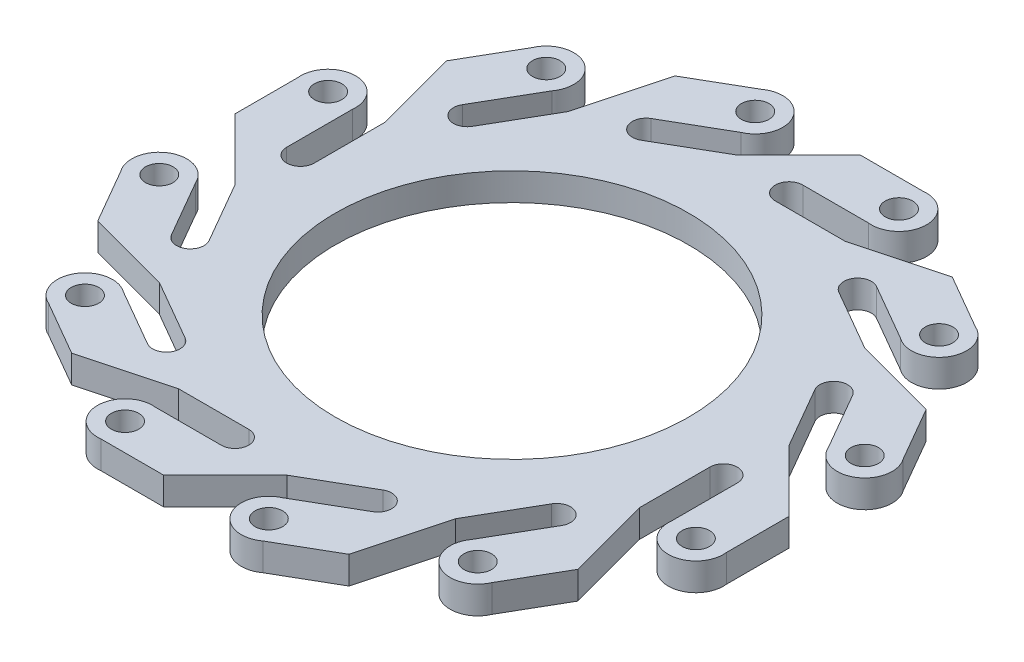
SolidWorks part; units mm, degrees
ref_plane "前视基准面" through (0, 0, 0) normal (0, 0, 1) x (1, 0, 0)
ref_plane "上视基准面" through (0, 0, 0) normal (0, 1, 0) x (1, 0, 0)
ref_plane "右视基准面" through (0, 0, 0) normal (1, 0, 0) x (0, 0, -1)
sketch "草图1" plane through (0, 0, 0) normal (0, 1, 0) x (1, 0, 0)
  line L0 (-31.2077, 0) -> (44.5556, 0) construction
  line L1 (0, 28.3069) -> (0, -34.4829) construction
  line L2 (7.1505, 22.7146) -> (2.5849, 22.7146)
  line L3 (7.1505, 18.7398) -> (2.3776, 18.7398)
  line L4 (2.3776, 16.7398) -> (7.4784, 16.7398)
  line L5 (10.429, 13.3082) -> (14.8463, 10.7579)
  line L6 (15.5624, 12.6539) -> (11.429, 15.0403)
  line L7 (17.5498, 16.0962) -> (13.5959, 18.379)
  line L8 (15.6859, 6.3108) -> (18.2362, 1.8934)
  line L9 (19.8043, 3.1774) -> (17.4179, 7.3108)
  line L10 (23.2466, 5.1648) -> (20.9639, 9.1187)
  line L11 (16.7398, -2.3776) -> (16.7398, -7.4784)
  line L12 (18.7398, -7.1505) -> (18.7398, -2.3776)
  line L13 (22.7146, -7.1505) -> (22.7146, -2.5849)
  line L14 (13.3082, -10.429) -> (10.7579, -14.8463)
  line L15 (12.6539, -15.5624) -> (15.0403, -11.429)
  line L16 (16.0962, -17.5498) -> (18.379, -13.5959)
  line L17 (6.3108, -15.6859) -> (1.8934, -18.2362)
  line L18 (3.1774, -19.8043) -> (7.3108, -17.4179)
  line L19 (5.1648, -23.2466) -> (9.1187, -20.9639)
  line L20 (-2.3776, -16.7398) -> (-7.4784, -16.7398)
  line L21 (-7.1505, -18.7398) -> (-2.3776, -18.7398)
  line L22 (-7.1505, -22.7146) -> (-2.5849, -22.7146)
  line L23 (-10.429, -13.3082) -> (-14.8463, -10.7579)
  line L24 (-15.5624, -12.6539) -> (-11.429, -15.0403)
  line L25 (-17.5498, -16.0962) -> (-13.5959, -18.379)
  line L26 (-15.6859, -6.3108) -> (-18.2362, -1.8934)
  line L27 (-19.8043, -3.1774) -> (-17.4179, -7.3108)
  line L28 (-23.2466, -5.1648) -> (-20.9639, -9.1187)
  line L29 (-16.7398, 2.3776) -> (-16.7398, 7.4784)
  line L30 (-18.7398, 7.1505) -> (-18.7398, 2.3776)
  line L31 (-22.7146, 7.1505) -> (-22.7146, 2.5849)
  line L32 (-13.3082, 10.429) -> (-10.7579, 14.8463)
  line L33 (-12.6539, 15.5624) -> (-15.0403, 11.429)
  line L34 (-16.0962, 17.5498) -> (-18.379, 13.5959)
  line L35 (-6.3108, 15.6859) -> (-1.8934, 18.2362)
  line L36 (-3.1774, 19.8043) -> (-7.3108, 17.4179)
  line L37 (-5.1648, 23.2466) -> (-9.1187, 20.9639)
  line L38 (2.5849, 22.7146) -> (-1.8934, 18.2362)
  line L39 (13.5959, 18.379) -> (7.4784, 16.7398)
  line L40 (20.9639, 9.1187) -> (14.8463, 10.7579)
  line L41 (22.7146, -2.5849) -> (18.2362, 1.8934)
  line L42 (18.379, -13.5959) -> (16.7398, -7.4784)
  line L43 (9.1187, -20.9639) -> (10.7579, -14.8463)
  line L44 (-2.5849, -22.7146) -> (1.8934, -18.2362)
  line L45 (-13.5959, -18.379) -> (-7.4784, -16.7398)
  line L46 (-20.9639, -9.1187) -> (-14.8463, -10.7579)
  line L47 (-22.7146, 2.5849) -> (-18.2362, -1.8934)
  line L48 (-18.379, 13.5959) -> (-16.7398, 7.4784)
  line L49 (-9.1187, 20.9639) -> (-10.7579, 14.8463)
  circle A0 centre (7.3746, 20.7272) radius 1
  circle A1 centre (0, 0) radius 22 construction
  arc A2 (7.1505, 22.7146) -> (7.1505, 18.7398) centre (7.3746, 20.7272) cw
  arc A3 (2.3776, 18.7398) -> (2.3776, 16.7398) centre (2.3776, 17.7398) ccw
  arc A4 (11.429, 15.0403) -> (10.429, 13.3082) centre (10.929, 14.1743) ccw
  arc A5 (17.5498, 16.0962) -> (15.5624, 12.6539) centre (16.7501, 14.263) cw
  circle A6 centre (16.7501, 14.263) radius 1
  arc A7 (17.4179, 7.3108) -> (15.6859, 6.3108) centre (16.5519, 6.8108) ccw
  arc A8 (23.2466, 5.1648) -> (19.8043, 3.1774) centre (21.6375, 3.977) cw
  circle A9 centre (21.6375, 3.977) radius 1
  arc A10 (18.7398, -2.3776) -> (16.7398, -2.3776) centre (17.7398, -2.3776) ccw
  arc A11 (22.7146, -7.1505) -> (18.7398, -7.1505) centre (20.7272, -7.3746) cw
  circle A12 centre (20.7272, -7.3746) radius 1
  arc A13 (15.0403, -11.429) -> (13.3082, -10.429) centre (14.1743, -10.929) ccw
  arc A14 (16.0962, -17.5498) -> (12.6539, -15.5624) centre (14.263, -16.7501) cw
  circle A15 centre (14.263, -16.7501) radius 1
  arc A16 (7.3108, -17.4179) -> (6.3108, -15.6859) centre (6.8108, -16.5519) ccw
  arc A17 (5.1648, -23.2466) -> (3.1774, -19.8043) centre (3.977, -21.6375) cw
  circle A18 centre (3.977, -21.6375) radius 1
  arc A19 (-2.3776, -18.7398) -> (-2.3776, -16.7398) centre (-2.3776, -17.7398) ccw
  arc A20 (-7.1505, -22.7146) -> (-7.1505, -18.7398) centre (-7.3746, -20.7272) cw
  circle A21 centre (-7.3746, -20.7272) radius 1
  arc A22 (-11.429, -15.0403) -> (-10.429, -13.3082) centre (-10.929, -14.1743) ccw
  arc A23 (-17.5498, -16.0962) -> (-15.5624, -12.6539) centre (-16.7501, -14.263) cw
  circle A24 centre (-16.7501, -14.263) radius 1
  arc A25 (-17.4179, -7.3108) -> (-15.6859, -6.3108) centre (-16.5519, -6.8108) ccw
  arc A26 (-23.2466, -5.1648) -> (-19.8043, -3.1774) centre (-21.6375, -3.977) cw
  circle A27 centre (-21.6375, -3.977) radius 1
  arc A28 (-18.7398, 2.3776) -> (-16.7398, 2.3776) centre (-17.7398, 2.3776) ccw
  arc A29 (-22.7146, 7.1505) -> (-18.7398, 7.1505) centre (-20.7272, 7.3746) cw
  circle A30 centre (-20.7272, 7.3746) radius 1
  arc A31 (-15.0403, 11.429) -> (-13.3082, 10.429) centre (-14.1743, 10.929) ccw
  arc A32 (-16.0962, 17.5498) -> (-12.6539, 15.5624) centre (-14.263, 16.7501) cw
  circle A33 centre (-14.263, 16.7501) radius 1
  arc A34 (-7.3108, 17.4179) -> (-6.3108, 15.6859) centre (-6.8108, 16.5519) ccw
  arc A35 (-5.1648, 23.2466) -> (-3.1774, 19.8043) centre (-3.977, 21.6375) cw
  circle A36 centre (-3.977, 21.6375) radius 1
  circle A37 centre (0, 0) radius 12.8351
  point P118 (0, 0)
  point P141 (0, 0)
  dimension "D1" = 44
  dimension "D2" = 2
  dimension "D3" = 2
  dimension "D4" = 1
  dimension "D9" = 25.6702
  dimension "D5" = 4.9969
  dimension "D7" = 135
  dimension "D6" = 12
  dimension "D8" = 12
extrude "凸台-拉伸1" add sketch "草图1" along normal blind 2
sketch "草图2" plane through (0, 0, 0) normal (0, -1, 0) x (1, 0, 0)
  line L0 (-3.0849, 22.7146) -> (-3.0849, 18.7398)
  line L1 (-7.1505, 22.7146) -> (-2.5849, 22.7146) construction
  line L2 (-2.3776, 18.7398) -> (-7.1505, 18.7398) construction
  dimension "D1" = 0.5
